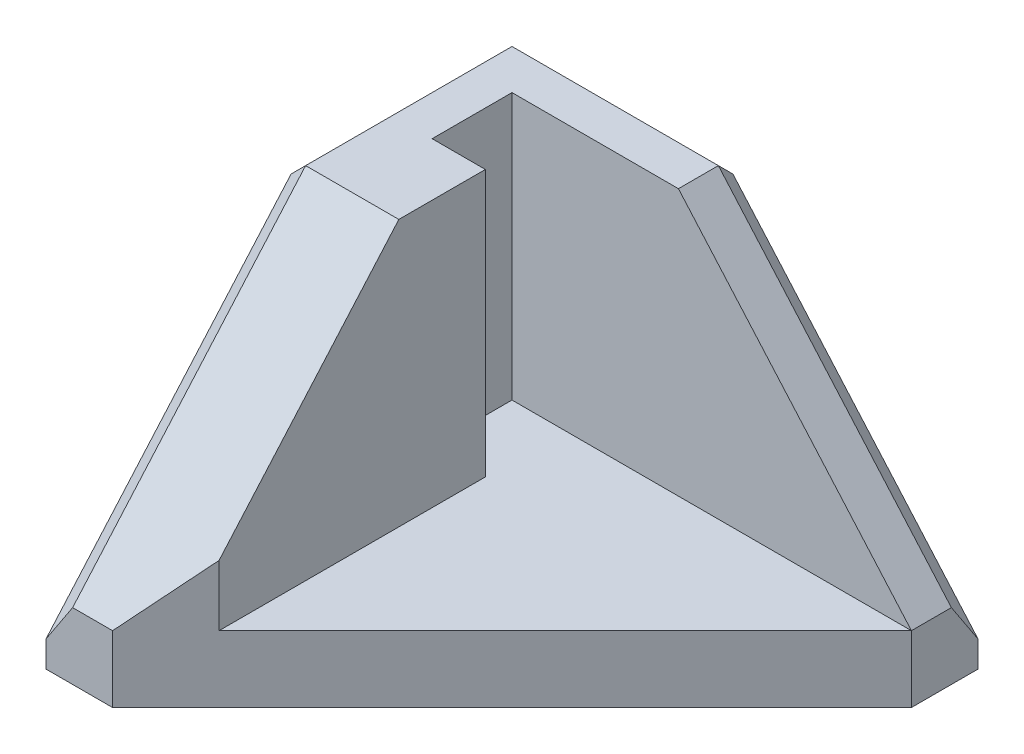
SolidWorks part; units mm, degrees
ref_plane "Front Plane" through (0, 0, 0) normal (0, 0, 1) x (1, 0, 0)
ref_plane "Top Plane" through (0, 0, 0) normal (0, 1, 0) x (1, 0, 0)
ref_plane "Right Plane" through (0, 0, 0) normal (1, 0, 0) x (0, 0, -1)
sketch "Sketch1" plane through (0, 0, 0) normal (0, 1, 0) x (1, 0, 0)
  line L0 (17.5, 12.5) -> (-12.5, -17.5)
  line L1 (-17.5, -17.5) -> (-12.5, -17.5)
  line L2 (-17.5, -17.5) -> (-17.5, 17.5)
  line L3 (-17.5, 17.5) -> (17.5, 17.5)
  line L4 (17.5, 12.5) -> (17.5, 17.5)
  line L5 (-17.5, -17.5) -> (17.5, 17.5) construction
  line L6 (-17.5, 17.5) -> (2.5, -2.5) construction
  point P0 (0, 0)
  dimension "D1" = 35
  dimension "D2" = 35
  dimension "D3" = 5
extrude "Boss-Extrude1" add sketch "Sketch1" along normal blind 5
sketch "Sketch2" plane through (0, 5, 0) normal (0, 1, 0) x (1, 0, 0)
  line L0 (-17.5, 17.5) -> (-17.5, -17.5) construction
  line L1 (17.5, 17.5) -> (-17.5, 17.5)
  line L2 (17.5, 17.5) -> (17.5, 12.5)
  line L3 (17.5, 12.5) -> (-12.5, 12.5)
  line L4 (-17.5, 17.5) -> (-17.5, 12.5)
  line L5 (-12.5, -17.5) -> (-8.5, -13.5)
  line L6 (-17.5, -17.5) -> (-12.5, -17.5)
  line L7 (-17.5, -17.5) -> (-17.5, 12.5)
  line L9 (-12.5, 6.5) -> (-12.5, 12.5)
  line L10 (-12.5, 6.5) -> (-8.5, 6.5)
  line L13 (-8.5, 6.5) -> (-8.5, -13.5)
  line L14 (-12.5, -17.5) -> (17.5, 12.5) construction
  point P12 (0, 0)
  point P14 (17.5, 12.5)
  dimension "D1" = 6
  dimension "D2" = 4
extrude "Boss-Extrude2" add sketch "Sketch2" along normal blind 20
sketch "Sketch3" plane through (0, 0, -17.5) normal (0, 0, -1) x (-1, 0, 0)
  line L0 (-17.5, 5) -> (0, 25)
  line L1 (-17.5, 25) -> (17.5, 25) construction
  line L2 (0, 25) -> (-17.5, 25)
  line L3 (-17.5, 25) -> (-17.5, 5)
extrude "Cut-Extrude1" cut sketch "Sketch3" against normal blind 20
sketch "Sketch4" plane through (-17.5, 0, 0) normal (-1, 0, 0) x (0, 0, 1)
  line L0 (17.5, 5) -> (0, 25)
  line L1 (17.5, 25) -> (17.5, 0) construction
  line L2 (-17.5, 25) -> (17.5, 25) construction
  line L3 (0, 25) -> (17.5, 25)
  line L4 (17.5, 25) -> (17.5, 5)
  line L5 (-17.5, 0) -> (17.5, 0) construction
  dimension "D1" = 5
extrude "Cut-Extrude2" cut sketch "Sketch4" against normal blind 20
chamfer "Chamfer1" distance 2 angle 45 4 edges at (8.75, 15, -17.5) (-8.75, 25, -17.5) (-17.5, 15, 8.75) (-17.5, 25, -8.75)
